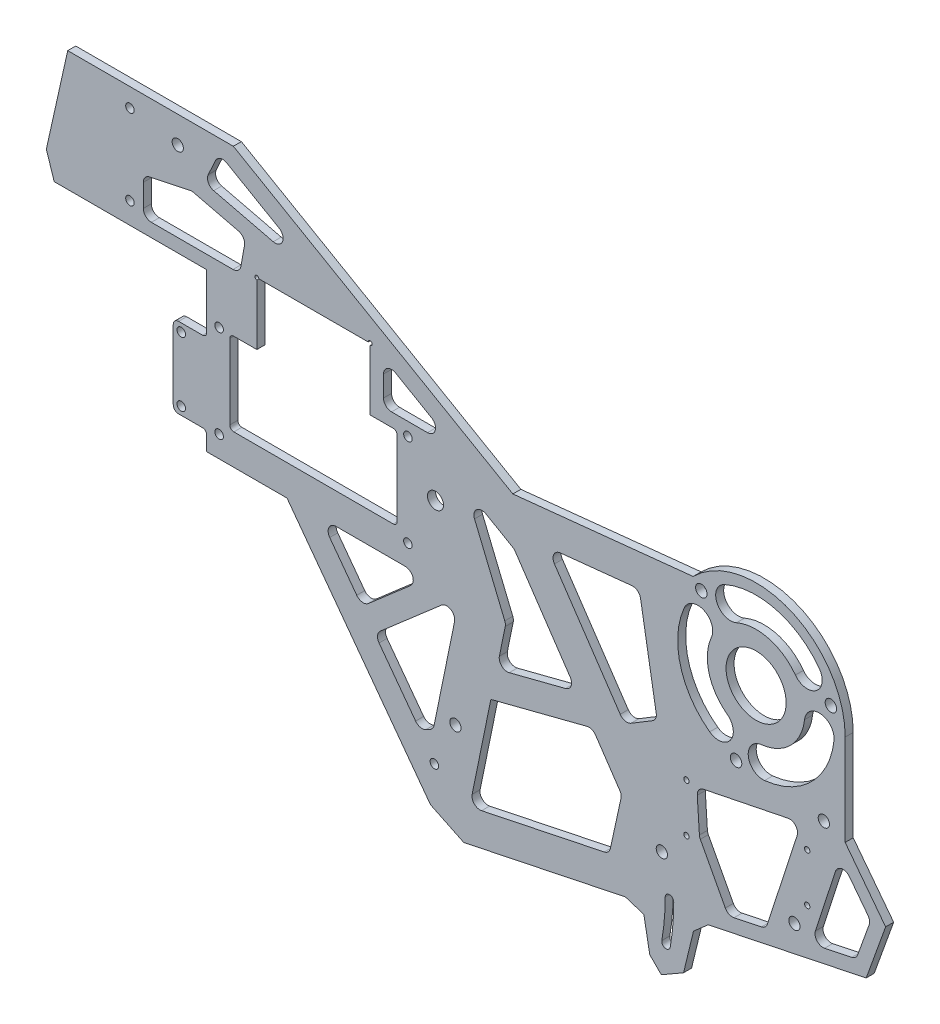
SolidWorks part; units mm, degrees
material "Thornel Mat VMA"
ref_plane "Front Plane" through (0, 0, 0) normal (0, 0, 1) x (1, 0, 0)
ref_plane "Top Plane" through (0, 0, 0) normal (0, 1, 0) x (1, 0, 0)
ref_plane "Right Plane" through (0, 0, 0) normal (1, 0, 0) x (0, 0, -1)
sketch "Sketch1" plane through (0, 0, 0) normal (0, 0, 1) x (1, 0, 0)
  line L1 (20.2869, 47.6) -> (204.7012, 47.6)
  line L2 (20.2869, 47.6) -> (20.2869, -36.0143)
  line L3 (20.2869, -36.0143) -> (204.7012, -36.0143)
  line L4 (204.7012, 47.6) -> (204.7012, -36.0143)
extrude "Boss-Extrude1" add sketch "Sketch1" along normal blind 3
sketch "Sketch2" plane through (0, 0, 0) normal (0, 0, -1) x (-1, 0, 0)
  circle A0 centre (-24.1169, 24) radius 3
  dimension "D1" = 6
extrude "Cut-Extrude1" cut sketch "Sketch2" against normal blind 70
sketch "Sketch3" plane through (0, 0, 3) normal (0, 0, 1) x (1, 0, 0)
  line L0 (24.1169, 24) -> (144.1169, 24) construction
  circle A0 centre (144.1169, 24) radius 11.25
  dimension "D2" = 22.5
  dimension "D1" = 120
extrude "Cut-Extrude2" cut sketch "Sketch3" against normal blind 3
sketch "Sketch4" plane through (0, 0, 3) normal (0, 0, 1) x (1, 0, 0)
  line L0 (-61.5431, 47.6) -> (-61.5431, -3) construction
  line L1 (-61.5431, 56) -> (-61.5431, 34)
  line L2 (-61.5431, 4) -> (-61.5431, -26)
  line L3 (-61.5431, 34) -> (-72.0431, 34)
  line L5 (-61.5431, 4) -> (-72.0431, 4)
  line L6 (-74.0431, 32) -> (-74.0431, 6)
  line L7 (-51.5431, 101) -> (-121.5431, 101)
  line L8 (-121.5431, 101) -> (-121.5431, 56)
  line L9 (-121.5431, 56) -> (-61.5431, 56)
  line L10 (-51.5431, 101) -> (40.9484, 47.6)
  line L11 (20.2869, 47.6) -> (20.2869, -36.0143)
  line L12 (20.2869, -36.0143) -> (204.7012, -36.0143)
  line L13 (204.7012, -36.0143) -> (204.7012, 47.6)
  line L14 (204.7012, 47.6) -> (20.2869, 47.6)
  line L15 (20.2869, 47.6) -> (20.2869, -36.0143)
  line L16 (20.2869, -36.0143) -> (204.7012, -36.0143)
  line L18 (40.9484, 47.6) -> (20.2869, 47.6)
  line L19 (-61.5431, -26) -> (34.7012, -81.5667)
  line L20 (34.7012, -81.5667) -> (204.7012, -81.5667)
  line L21 (204.7012, -81.5667) -> (204.7012, -36.0143)
  line L22 (-85.0431, 56) -> (-64.7431, 56) construction
  circle A0 centre (-71.0431, 31) radius 1.6
  circle A1 centre (-71.0431, 7) radius 1.6
  arc A2 (-72.0431, 4) -> (-74.0431, 6) centre (-72.0431, 6) cw
  arc A3 (-72.0431, 34) -> (-74.0431, 32) centre (-72.0431, 32) ccw
  dimension "D1" = 3.2
  dimension "D2" = 3
  dimension "D5" = 2
  dimension "D3" = 3
  dimension "D4" = 3
  dimension "D7" = 60
  dimension "D8" = 45
  dimension "D9" = 30
  dimension "D10" = 30
  dimension "D11" = 70
  dimension "D12" = 170
  dimension "D6" = 0
extrude "Boss-Extrude2" add sketch "Sketch4" against normal blind 3
sketch "Sketch5" plane through (0, 0, 3) normal (0, 0, 1) x (1, 0, 0)
  line L0 (-0.5431, 62.6) -> (-42.5431, 62.6) construction
  line L1 (8.2869, 8.5) -> (-51.3731, 8.5)
  line L2 (9.7869, 10) -> (9.7869, 38)
  line L3 (8.2869, 39.5) -> (-0.3431, 39.5)
  line L4 (-52.8731, 10) -> (-52.8731, 38)
  line L5 (-41.9931, 62.8) -> (-1.0931, 62.8)
  line L6 (-42.7431, 62.05) -> (-42.7431, 39.5)
  line L8 (-0.3431, 62.05) -> (-0.3431, 39.5)
  line L9 (-42.5431, 57.6) -> (-42.5431, 52.6) construction
  line L10 (-0.5431, 62.6) -> (-0.5431, 57.6) construction
  line L11 (-42.7431, 39.5) -> (-51.3731, 39.5)
  line L13 (7.7869, 47.6) -> (7.7869, -3) construction
  line L14 (-50.8731, -3) -> (-50.8731, 47.6) construction
  line L15 (8.4569, 34.5) -> (-51.5431, 34.5) construction
  line L16 (-51.5431, 13.5) -> (8.4569, 13.5) construction
  arc A0 (9.7869, 38) -> (8.2869, 39.5) centre (8.2869, 38) ccw
  arc A1 (8.2869, 8.5) -> (9.7869, 10) centre (8.2869, 10) ccw
  arc A2 (-51.3731, 8.5) -> (-52.8731, 10) centre (-51.3731, 10) cw
  arc A3 (-51.3731, 39.5) -> (-52.8731, 38) centre (-51.3731, 38) ccw
  arc A4 (-41.9931, 62.8) -> (-42.7431, 62.05) centre (-42.7431, 62.8) ccw
  arc A6 (-1.0931, 62.8) -> (-0.3431, 62.05) centre (-0.3431, 62.8) cw
  dimension "D8" = 1.5
  dimension "D9" = 1.5
  dimension "D10" = 0.75
  dimension "D1" = 0.2
  dimension "D2" = 0.2
  dimension "D3" = 0.2
  dimension "D4" = 2
  dimension "D5" = 2
  dimension "D6" = 5
  dimension "D7" = 5
extrude "Cut-Extrude3" cut sketch "Sketch5" against normal blind 10 contours L8 L5 L6 L3 | L4 L1 L2 L3
sketch "Sketch6" plane through (0, 0, 3) normal (0, 0, 1) x (1, 0, 0)
  line L0 (-61.5431, -3) -> (-50.8731, -3) construction
  line L1 (13.7869, 5) -> (-56.8731, 5) construction
  line L2 (13.7869, 5) -> (13.7869, 39.6) construction
  line L3 (13.7869, 39.6) -> (-56.8731, 39.6) construction
  line L4 (-56.8731, 5) -> (-56.8731, 39.6) construction
  line L5 (-61.5431, 47.6) -> (-50.8731, 47.6) construction
  line L6 (-52.8731, 10) -> (-52.8731, 38) construction
  line L7 (9.7869, 10) -> (9.7869, 38) construction
  circle A0 centre (13.7869, 5) radius 1.6
  circle A1 centre (13.7869, 39.6) radius 1.6
  circle A2 centre (-56.8731, 5) radius 1.6
  circle A3 centre (-56.8731, 39.6) radius 1.6
  dimension "D5" = 3.2
  dimension "D1" = 8
  dimension "D2" = 8
  dimension "D3" = 4
  dimension "D4" = 4
extrude "Cut-Extrude4" cut sketch "Sketch6" against normal blind 3
fillet "Fillet1" radius 1.5 2 edges at (-61.5431, 4, 1.5) (-61.5431, 34, 1.5)
sketch "Sketch8" plane through (0, 0, 3) normal (0, 0, 1) x (1, 0, 0)
  circle A0 centre (-90.2431, 94) radius 1.6
  circle A1 centre (-90.2431, 64) radius 1.6
  dimension "D1" = 3.2
extrude "Cut-Extrude6" cut sketch "Sketch8" against normal blind 12
sketch "Sketch9" plane through (0, 0, 0) normal (0, 0, -1) x (-1, 0, 0)
  circle A0 centre (-172.1287, 31.5058) radius 2.15
  circle A1 centre (-123.6108, 44.5061) radius 2.15
  circle A2 centre (-136.6111, -4.0118) radius 2.15
  dimension "D1" = 4.3
extrude "Cut-Extrude7" cut sketch "Sketch9" against normal blind 12
sketch "Sketch10" plane through (0, 0, 0) normal (0, 0, -1) x (-1, 0, 0)
  line L0 (-204.7012, 47.6) -> (-40.9484, 47.6) construction
  line L1 (-167.6809, 47.6) -> (-120.5529, 47.6)
  arc A0 (-120.5529, 47.6) -> (-167.6809, 47.6) centre (-144.1169, 24) ccw
  dimension "D1" = 66.7
extrude "Boss-Extrude3" add sketch "Sketch10" against normal blind 3
sketch "Sketch12" plane through (0, 0, 3) normal (0, 0, 1) x (1, 0, 0)
  line L0 (34.7012, -81.5667) -> (204.7012, -81.5667) construction
  circle A0 centre (23.7012, -61.5667) radius 1.6
  arc A1 (111.7012, -61.5667) -> (110.4134, -76.5667) centre (23.7012, -61.5667) cw construction
  arc A2 (110.1012, -61.5667) -> (108.8368, -76.294) centre (23.7012, -61.5667) cw
  arc A3 (113.3012, -61.5667) -> (111.99, -76.8394) centre (23.7012, -61.5667) cw
  arc A4 (113.3012, -61.5667) -> (110.1012, -61.5667) centre (111.7012, -61.5667) ccw
  arc A5 (111.99, -76.8394) -> (108.8368, -76.294) centre (110.4134, -76.5667) cw
  dimension "D1" = 3.2
  dimension "D2" = 1.6
  dimension "D3" = 5
extrude "Cut-Extrude8" cut sketch "Sketch12" against normal blind 10
sketch "Sketch13" plane through (0, 0, 0) normal (0, 0, -1) x (-1, 0, 0)
  circle A0 centre (-163.2569, -19.6667) radius 1
  circle A1 centre (-163.2569, -37.6667) radius 1
  circle A2 centre (-118.0569, -19.6667) radius 1
  circle A3 centre (-118.0569, -37.6667) radius 1
  dimension "D1" = 2
extrude "Cut-Extrude9" cut sketch "Sketch13" against normal blind 10
sketch "Sketch14" plane through (0, 0, 3) normal (0, 0, 1) x (1, 0, 0)
  line L0 (-78.9115, 93.4551) -> (-78.9115, 81.4862)
  line L1 (-78.9115, 81.4862) -> (-54.4003, 81.4862)
  line L2 (-54.4003, 81.4862) -> (-23.8974, 71.6817)
  line L3 (-23.8974, 71.6817) -> (-52.5178, 93.4551)
  line L4 (-52.5178, 93.4551) -> (-78.9115, 93.4551)
  line L5 (-78.9115, 72.578) -> (-70.6821, 62.8507)
  line L6 (-70.6821, 62.8507) -> (-60.2008, 63.6802)
  line L7 (-60.2008, 63.6802) -> (-54.4003, 58.7304)
  line L8 (-54.4003, 58.7304) -> (-54.4003, 45.3567)
  line L9 (-54.4003, 45.3567) -> (-47.2283, 45.9243)
  line L10 (-47.2283, 45.9243) -> (-47.2283, 69.3356)
  line L11 (-47.2283, 69.3356) -> (-63.8202, 74.1615)
  line L12 (-63.8202, 74.1615) -> (-78.9115, 72.578)
  line L13 (4.6513, 57.6299) -> (6.1633, 43.2207)
  line L14 (6.1633, 43.2207) -> (24.148, 52.0435)
  line L15 (24.148, 52.0435) -> (4.6513, 57.6299)
  line L16 (-45.3699, 1.9614) -> (-38.5507, -11.9389)
  line L17 (-38.5507, -11.9389) -> (-7.827, 0.9897)
  line L18 (-7.827, 0.9897) -> (-45.3699, 1.9614)
  line L19 (25.5976, 0.9897) -> (-23.1889, -25.4945)
  line L20 (-23.1889, -25.4945) -> (15.1557, -49.1549)
  line L21 (15.1557, -49.1549) -> (22.7058, -35.0463)
  line L22 (22.7058, -35.0463) -> (25.5976, 0.9897)
  line L23 (40.0766, 31.4181) -> (50.4041, -2.9024)
  line L24 (50.4041, -2.9024) -> (40.0766, -53.4167)
  line L25 (40.0766, -53.4167) -> (100.5808, -42.9603)
  line L26 (100.5808, -42.9603) -> (93.2786, -7.1794)
  line L27 (93.2786, -7.1794) -> (104.3379, 31.4181)
  line L28 (104.3379, 31.4181) -> (40.0766, 31.4181)
  line L29 (128.8509, 35.2778) -> (117.8298, 30.6401)
  line L30 (117.8298, 30.6401) -> (110.8301, -3.5975)
  line L31 (110.8301, -3.5975) -> (123.3404, -3.5975)
  line L32 (123.3404, -3.5975) -> (126.888, 28.7882)
  line L33 (126.888, 28.7882) -> (129.9965, 31.4181)
  line L34 (129.9965, 31.4181) -> (128.8509, 35.2778)
  line L35 (108.9142, -14.8646) -> (113.6543, -38.091)
  line L36 (113.6543, -38.091) -> (133.5452, -30.7552)
  line L37 (133.5452, -30.7552) -> (123.8212, -12.8427)
  line L38 (123.8212, -12.8427) -> (108.9142, -14.8646)
  line L39 (132.2934, -12.8427) -> (142.2048, -27.2848)
  line L40 (142.2048, -27.2848) -> (145.1405, -21.7989)
  line L41 (145.1405, -21.7989) -> (132.2934, -12.8427)
  line L42 (134.3797, 10.2416) -> (133.5452, 2.6233)
  line L43 (133.5452, 2.6233) -> (157.3171, -7.1794)
  line L44 (157.3171, -7.1794) -> (160.734, -2.2781)
  line L45 (160.734, -2.2781) -> (134.3797, 10.2416)
  line L46 (175.8668, 40.8797) -> (188.507, 15.1137)
  line L47 (188.507, 15.1137) -> (177.3665, -23.7672)
  line L48 (177.3665, -23.7672) -> (157.3171, -46.7471)
  line L49 (157.3171, -46.7471) -> (120.319, -62.316)
  line L50 (120.319, -62.316) -> (116.3677, -89.9345)
  line L51 (116.3677, -89.9345) -> (104.3379, -88.2135)
  line L52 (104.3379, -88.2135) -> (104.3379, -66.6352)
  line L53 (104.3379, -66.6352) -> (10.5955, -82.8358)
sketch "Sketch16" plane through (0, 0, 3) normal (0, 0, 1) x (1, 0, 0)
  line L0 (185.3256, -50.1785) -> (192.6101, -29.967)
  line L1 (192.6101, -29.967) -> (177.4666, -10.1551)
  line L2 (177.4666, -10.1551) -> (177.4669, 23.9998)
  line L3 (185.3256, -50.1785) -> (126.1767, -62.5044)
  line L4 (126.1767, -62.5044) -> (120.6914, -67.2922)
  line L5 (120.6914, -67.2922) -> (116.9293, -82.819)
  line L6 (116.9293, -82.819) -> (107.0809, -86.6499)
  line L7 (107.0809, -86.6499) -> (104.3379, -83.2478)
  line L8 (104.3379, -83.2478) -> (102.1139, -71.1635)
  line L9 (102.1139, -71.1635) -> (95.1728, -68.9652)
  line L10 (95.1728, -68.9652) -> (34.7012, -81.5667)
  line L11 (34.7012, -81.5667) -> (-10.3776, -59.7831)
  line L12 (-10.3776, -59.7831) -> (-61.5431, 0.5)
  line L13 (-61.5431, 2.5) -> (-61.5431, -26) construction
  line L14 (167.6809, 47.6) -> (204.7012, 47.6)
  line L15 (204.7012, 47.6) -> (204.7012, -81.5667)
  line L16 (204.7012, -81.5667) -> (109.0158, -101.5063)
  line L17 (109.0158, -101.5063) -> (-44.9012, -81.5667)
  line L18 (-44.9012, -81.5667) -> (-83.4799, -7.1794)
  line L19 (-83.4799, -7.1794) -> (-61.5431, 0.5)
  line L20 (181.5695, -45.8538) -> (186.9817, -30.837)
  line L21 (186.9817, -30.837) -> (175.5875, -15.9302)
  line L22 (175.5875, -15.9302) -> (164.7077, -49.3676)
  line L23 (164.7077, -49.3676) -> (181.5695, -45.8538)
  line L24 (147.7862, -52.8938) -> (133.6464, -55.8404)
  line L25 (133.6464, -55.8404) -> (122.94, -35.6877)
  line L26 (122.94, -35.6877) -> (121.9284, -19.9448)
  line L27 (121.9284, -19.9448) -> (161.094, -11.9946)
  line L28 (161.094, -11.9946) -> (147.7862, -52.8938)
  line L29 (89.1667, -57.959) -> (93.8268, -36.5614)
  line L30 (93.8268, -36.5614) -> (82.8591, -20.3346)
  line L31 (82.8591, -20.3346) -> (44.8433, -30.1016)
  line L32 (44.8433, -30.1016) -> (36.9222, -68.8461)
  line L33 (36.9222, -68.8461) -> (89.1667, -57.959)
  line L34 (76.9131, -11.5374) -> (47.0712, -19.2044)
  line L35 (47.0712, -19.2044) -> (50.4041, -2.9024)
  line L36 (50.4041, -2.9024) -> (35.3223, 33.6)
  line L37 (35.3223, 33.6) -> (46.4046, 33.6)
  line L38 (46.4046, 33.6) -> (76.9131, -11.5374)
  line L39 (94.8609, -13.0907) -> (107.0873, -5.7113)
  line L40 (107.0873, -5.7113) -> (100.3631, 33.6)
  line L41 (100.3631, 33.6) -> (63.3026, 33.6)
  line L42 (63.3026, 33.6) -> (94.8609, -13.0907)
  line L43 (12.3235, -57.4254) -> (22.136, -41.3202)
  line L44 (22.136, -41.3202) -> (30.031, -2.7036)
  line L45 (30.031, -2.7036) -> (-25.069, -30.1108)
  line L46 (-25.069, -30.1108) -> (-11.7658, -45.7846)
  line L47 (-11.7658, -45.7846) -> (12.3235, -57.4254)
  line L48 (-31.7345, -22.2575) -> (1.7886, -5.5828)
  line L49 (1.7886, -5.5828) -> (-2.1286, 0.5)
  line L50 (-2.1286, 0.5) -> (-41.5431, 0.5)
  line L51 (-41.5431, 0.5) -> (-41.5431, -10.701)
  line L52 (-41.5431, -10.701) -> (-31.7345, -22.2575)
  line L53 (32.3178, 44.5) -> (4.6569, 44.5)
  line L54 (4.6569, 44.5) -> (4.6569, 60.47)
  line L55 (4.6569, 60.47) -> (32.3178, 44.5)
  line L56 (-16.3481, 72.5973) -> (-56.8804, 95.9986)
  line L57 (-56.8804, 95.9986) -> (-62.4567, 83.7818)
  line L58 (-62.4567, 83.7818) -> (-16.3481, 72.5973)
  line L59 (-49.1617, 61) -> (-46.8615, 73.8249)
  line L60 (-46.8615, 73.8249) -> (-67.0805, 78.7295)
  line L61 (-67.0805, 78.7295) -> (-85.2431, 74.8953)
  line L62 (-85.2431, 74.8953) -> (-85.2431, 61)
  line L63 (-85.2431, 61) -> (-49.1617, 61)
  line L65 (110.4134, -76.5667) -> (116.9293, -82.819) construction
  line L66 (110.4134, -76.5667) -> (104.3379, -83.2478) construction
  line L67 (120.6914, -67.2922) -> (102.1139, -71.1635) construction
  line L68 (8.2869, 8.5) -> (-51.3731, 8.5) construction
  line L69 (50.4041, -2.9024) -> (40.0766, -53.4167) construction
  line L70 (104.3379, -88.2135) -> (104.3379, -66.6352) construction
  line L72 (8.2869, 39.5) -> (-0.3431, 39.5) construction
  line L73 (-0.3431, 62.05) -> (-0.3431, 39.5) construction
  line L74 (40.9484, 47.6) -> (-51.5431, 101) construction
  line L75 (-121.5431, 56) -> (-61.5431, 56) construction
  line L76 (120.5529, 47.6) -> (40.9484, 47.6) construction
  circle A0 centre (144.1169, 24) radius 33.35 construction
  arc A1 (177.4669, 23.9998) -> (167.6809, 47.6) centre (144.1169, 24) ccw
  circle A2 centre (106.5214, -50.3836) radius 2.1 construction
  circle A3 centre (164.7077, -10.5397) radius 2.1 construction
  circle A4 centre (30.031, -49.0844) radius 2.1 construction
  circle A5 centre (-75.4287, 89.9176) radius 2.1 construction
  circle A6 centre (163.2569, -37.6667) radius 1 construction
  circle A7 centre (118.0569, -37.6667) radius 1 construction
  circle A8 centre (-90.2431, 64) radius 1.6 construction
  arc A9 (-41.9931, 62.8) -> (-42.7431, 62.05) centre (-42.7431, 62.8) ccw construction
  dimension "D1" = 4.2
  dimension "D5" = 5
  dimension "D2" = 5
  dimension "D3" = 5
  dimension "D4" = 5
  dimension "D6" = 15
  dimension "D7" = 5
  dimension "D8" = 12
  dimension "D9" = 10
  dimension "D10" = 14
  dimension "D11" = 8
  dimension "D12" = 10
  dimension "D13" = 8
  dimension "D14" = 20
  dimension "D15" = 20
  dimension "D16" = 12
  dimension "D17" = 5
  dimension "D18" = 5
  dimension "D19" = 7
  dimension "D20" = 5
  dimension "D21" = 5
  dimension "D22" = 6
  dimension "D23" = 6
  dimension "D24" = 14
  dimension "D25" = 2
extrude "Cut-Extrude10" cut sketch "Sketch16" against normal blind 10
fillet "Fillet2" radius 3 43 edges at (175.5875, -15.9302, 1.5) (186.9817, -30.837, 1.5) (164.7077, -49.3676, 1.5) (181.5695, -45.8538, 1.5) (121.9284, -19.9448, 1.5) (122.94, -35.6877, 1.5) (133.6464, -55.8404, 1.5) (147.7862, -52.8938, 1.5) (94.8609, -13.0907, 1.5) (63.3026, 33.6, 1.5) (35.3223, 33.6, 1.5) (76.9131, -11.5374, 1.5) (89.1667, -57.959, 1.5) (36.9222, -68.8461, 1.5) (50.4041, -2.9024, 1.5) (47.0712, -19.2044, 1.5) (93.8268, -36.5614, 1.5) (82.8591, -20.3346, 1.5) (107.0873, -5.7113, 1.5) (100.3631, 33.6, 1.5) (161.094, -11.9946, 1.5) (46.4046, 33.6, 1.5) (30.031, -2.7036, 1.5) (-25.069, -30.1108, 1.5) (22.136, -41.3202, 1.5) (12.3235, -57.4254, 1.5) (-11.7658, -45.7846, 1.5) (-41.5431, -10.701, 1.5) (-31.7345, -22.2575, 1.5) (1.7886, -5.5828, 1.5) (-2.1286, 0.5, 1.5) (-41.5431, 0.5, 1.5) (4.6569, 60.47, 1.5) (32.3178, 44.5, 1.5) (4.6569, 44.5, 1.5) (-85.2431, 61, 1.5) (-46.8615, 73.8249, 1.5) (-49.1617, 61, 1.5) (-67.0805, 78.7295, 1.5) (-85.2431, 74.8953, 1.5) (-56.8804, 95.9986, 1.5) (-62.4567, 83.7818, 1.5) (-16.3481, 72.5973, 1.5)
sketch "Sketch17" plane through (0, 0, 3) normal (0, 0, 1) x (1, 0, 0)
  line L0 (34.7012, -81.5667) -> (-10.3776, -59.7831)
  line L1 (-10.3776, -59.7831) -> (-17.4388, -51.4637)
  line L2 (-17.4388, -51.4637) -> (-61.5431, 0.5) construction
  line L3 (-11.1945, -46.0607) -> (9.8726, -56.241) construction
  line L4 (-17.4388, -51.4637) -> (34.7012, -81.5667) construction
  line L5 (-17.4388, -51.4637) -> (34.7012, -81.5667)
extrude "Boss-Extrude4" add sketch "Sketch17" against normal blind 3
sketch "Sketch18" plane through (0, 0, 3) normal (0, 0, 1) x (1, 0, 0)
  line L0 (-51.5431, 101) -> (-121.5431, 101) construction
  line L1 (-58.251, 92.9958) -> (-60.9482, 87.0866) construction
  line L2 (13.7398, -55.1008) -> (21.8636, -41.7673) construction
  line L3 (44.8433, -30.1016) -> (37.8357, -64.3779) construction
  line L4 (89.5808, -56.0575) -> (93.5536, -37.8159) construction
  line L5 (123.2431, -36.2582) -> (132.5898, -53.8515) construction
  line L6 (173.8201, -21.362) -> (166.3088, -44.4468) construction
  line L7 (177.4669, 23.9998) -> (177.4666, -10.1551) construction
  line L8 (156.0528, -13.0179) -> (124.4933, -19.4241) construction
  circle A0 centre (31.5838, -45.033) radius 2.1
  circle A1 centre (-72.3529, 91) radius 2.1
  circle A2 centre (108.8401, -47.5134) radius 2.1
  circle A3 centre (158.4664, -45.9257) radius 2.1
  circle A4 centre (144.1169, 24) radius 33.35 construction
  circle A5 centre (169.4666, -7.2338) radius 2.1
  dimension "D1" = 4.2
  dimension "D2" = 10
  dimension "D3" = 12
  dimension "D4" = 10
  dimension "D5" = 10
  dimension "D6" = 17
  dimension "D7" = 18
  dimension "D8" = 7
  dimension "D9" = 19
  dimension "D10" = 8
  dimension "D11" = 3
extrude "Cut-Extrude11" cut sketch "Sketch18" against normal blind 3
sketch "Sketch19" plane through (0, 0, 3) normal (0, 0, 1) x (1, 0, 0)
  circle A0 centre (144.1169, 24) radius 29.35
  circle A1 centre (144.1169, 24) radius 18.25
  arc A2 (132.3018, 50.8668) -> (136.7702, 40.706) centre (134.536, 45.7864) ccw
  arc A3 (167.7824, 41.3598) -> (158.8323, 34.7944) centre (163.3073, 38.0771) cw
  arc A4 (162.258, 22.0094) -> (173.2918, 20.7987) centre (167.7749, 21.4041) cw
  arc A5 (146.1075, 5.8589) -> (147.3182, -5.1749) centre (146.7128, 0.342) ccw
  arc A6 (133.3224, 9.2846) -> (126.757, 0.3344) centre (130.0397, 4.8095) cw
  arc A7 (127.4109, 31.3467) -> (117.25, 35.8151) centre (122.3305, 33.5809) ccw
  arc A8 (177.4669, 23.9998) -> (120.5529, 47.6) centre (144.1169, 24) ccw construction
  circle A9 centre (144.1169, 24) radius 11.25 construction
  circle A10 centre (172.1287, 31.5058) radius 2.15 construction
  circle A11 centre (123.6108, 44.5061) radius 2.15 construction
  circle A12 centre (136.6111, -4.0118) radius 2.15 construction
  dimension "D1" = 4
  dimension "D2" = 7
  dimension "D8" = 11
  dimension "D3" = 11
  dimension "D4" = 11
  dimension "D5" = 11
  dimension "D6" = 11
  dimension "D7" = 11
extrude "Cut-Extrude12" cut sketch "Sketch19" against normal blind 3 contours A3 A0 A2 A1 | A1 A7 A0 A6 | A1 A5 A0 A4
sketch "Sketch20" plane through (0, 0, 3) normal (0, 0, 1) x (1, 0, 0)
  line L4 (-121.5431, 101) -> (-113.5431, 101)
  line L5 (-113.5431, 101) -> (-121.5431, 65.0628)
  line L6 (-121.5431, 65.0628) -> (-118.5984, 56)
  line L7 (-118.5984, 56) -> (-121.5431, 56)
  line L8 (-121.5431, 56) -> (-121.5431, 101)
  line L9 (-121.5431, 101) -> (-121.5431, 56) construction
  line L10 (-121.5431, 56) -> (-61.5431, 56) construction
  line L11 (-51.5431, 101) -> (-121.5431, 101) construction
  dimension "D2" = 72
  dimension "D3" = 77.45
  dimension "D4" = 8
extrude "Cut-Extrude13" cut sketch "Sketch20" against normal blind 10 contours L8 L5 L4 | L8 L7 L6
sketch "Sketch21" plane through (0, 0, 3) normal (0, 0, 1) x (1, 0, 0)
  line L0 (117.2327, -81.5667) -> (116.9665, -82.6658)
  line L1 (116.9665, -82.6658) -> (108.6575, -87.4629)
  line L2 (108.6575, -87.4629) -> (104.3143, -83.1198)
  line L3 (104.3143, -83.1198) -> (104.0285, -81.5667)
  line L4 (104.0285, -81.5667) -> (117.2327, -81.5667)
  line L5 (120.6914, -67.2922) -> (117.2327, -81.5667) construction
  line L6 (104.0285, -81.5667) -> (102.1139, -71.1635) construction
  line L7 (110.4134, -76.5667) -> (116.9665, -82.6658) construction
  line L8 (104.3143, -83.1198) -> (110.4134, -76.5667) construction
  dimension "D1" = 30
  dimension "D2" = 45
extrude "Boss-Extrude5" add sketch "Sketch21" against normal blind 3
sketch "Sketch22" plane through (0, 0, 3) normal (0, 0, 1) x (1, 0, 0)
  line L0 (22.246, -75.5479) -> (-29.7449, -5.3216)
  line L1 (-29.7449, -5.3216) -> (-61.5431, -5.3216)
  line L2 (-61.5431, -5.3216) -> (-61.5431, 0.5)
  line L4 (-61.5431, 2.5) -> (-61.5431, 0.5) construction
  line L6 (-10.3776, -59.7831) -> (34.7012, -81.5667) construction
  line L7 (22.246, -75.5479) -> (-101.253, -52.9562)
  line L8 (-101.253, -52.9562) -> (-61.5431, 0.5)
extrude "Cut-Extrude14" cut sketch "Sketch22" against normal blind 10
sketch "Sketch23" plane through (0, 0, 3) normal (0, 0, 1) x (1, 0, 0)
  line L0 (22.246, -75.5479) -> (-31.4636, -3)
  line L1 (-31.4636, -3) -> (-61.5431, -3)
  line L3 (-15.0734, -25.139) -> (-21.1166, -16.9761) construction
  line L4 (22.246, -75.5479) -> (19.933, -56.2587)
  line L5 (19.933, -56.2587) -> (25.986, -38.1223)
  line L6 (25.986, -38.1223) -> (34.1858, 1.8113)
  line L7 (34.1858, 1.8113) -> (9.3649, -1.4066)
  line L8 (9.3649, -1.4066) -> (0.0796, 0.5)
  line L9 (0.0796, 0.5) -> (-61.5431, 0.5)
  line L10 (-61.5431, 0.5) -> (-61.5431, -3)
  line L11 (-74.0431, 32) -> (-74.0431, 6) construction
  line L12 (-51.5431, 101) -> (-113.5431, 101) construction
  dimension "D1" = 42.5795
  dimension "D2" = 74.1227
  dimension "D3" = 83.408
  dimension "D4" = 93.9761
  dimension "D5" = 100.0291
  dimension "D6" = 108.2289
  dimension "D7" = 99.1887
  dimension "D8" = 102.4066
  dimension "D10" = 157.2587
extrude "Boss-Extrude7" add sketch "Sketch23" against normal blind 3
sketch "Sketch24" plane through (0, 0, 3) normal (0, 0, 1) x (1, 0, 0)
  line L0 (-41.5431, -3) -> (-58.5725, -3)
  line L1 (-58.5725, -3) -> (-58.5725, -18.775)
  line L2 (-58.5725, -18.775) -> (-41.5431, -18.775)
  line L3 (-41.5431, -18.775) -> (-41.5431, -3)
extrude "Cut-Extrude15" cut sketch "Sketch24" against normal blind 3
sketch "Sketch25" plane through (0, 0, 3) normal (0, 0, 1) x (1, 0, 0)
  line L0 (16.6752, -51.2169) -> (2.9955, -32.7392)
  line L1 (3.44, -28.6886) -> (26.3557, -8.796)
  line L2 (31.2615, -11.6624) -> (23.5944, -49.1642)
  line L3 (22.1083, -51.1879) -> (20.5394, -52.0565)
  line L4 (-0.9821, -21.9336) -> (14.7631, -8.2655)
  line L5 (12.7965, -3) -> (-13.0677, -3)
  line L6 (-15.4789, -7.785) -> (-5.3599, -21.4532)
  line L7 (44.8433, -30.1016) -> (37.8357, -64.3779) construction
  line L8 (8.2869, 8.5) -> (-51.3731, 8.5) construction
  line L9 (22.246, -75.5479) -> (-31.4636, -3) construction
  line L10 (-61.5431, -3) -> (-31.4636, -3) construction
  line L11 (-74.0431, 32) -> (-74.0431, 6) construction
  circle A0 centre (31.5838, -45.033) radius 2.1 construction
  arc A1 (-13.0677, -3) -> (-15.4789, -7.785) centre (-13.0677, -6) ccw
  arc A2 (-0.9821, -21.9336) -> (-5.3599, -21.4532) centre (-2.9488, -19.6681) cw
  arc A3 (14.7631, -8.2655) -> (12.7965, -3) centre (12.7965, -6) ccw
  arc A4 (2.9955, -32.7392) -> (3.44, -28.6886) centre (5.4066, -30.9541) cw
  arc A5 (26.3557, -8.796) -> (31.2615, -11.6624) centre (28.3223, -11.0615) cw
  arc A6 (16.6752, -51.2169) -> (20.5394, -52.0565) centre (19.0863, -49.4318) ccw
  arc A7 (23.5944, -49.1642) -> (22.1083, -51.1879) centre (20.6552, -48.5633) cw
  point P23 (-19.0214, -3)
  point P26 (-3.4306, -24.0591)
  point P31 (1.3439, -30.5082)
  point P34 (33.0325, -3)
  point P37 (18.2394, -53.3298)
  point P40 (23.3175, -50.5184)
  dimension "D5" = 3
  dimension "D1" = 10
  dimension "D2" = 7
  dimension "D3" = 8
  dimension "D4" = 70.6125
  dimension "D6" = 92.2825
  dimension "D8" = 97.3607
extrude "Cut-Extrude16" cut sketch "Sketch25" against normal blind 3
sketch "Sketch26" plane through (0, 0, 3) normal (0, 0, 1) x (1, 0, 0)
  line L0 (40.9484, 47.6) -> (53.0727, 40.6)
  line L1 (53.0727, 40.6) -> (120.5529, 47.6)
  line L2 (40.9484, 47.6) -> (120.5529, 47.6)
  line L3 (40.9484, 47.6) -> (-51.5431, 101) construction
  dimension "D1" = 7
extrude "Cut-Extrude17" cut sketch "Sketch26" against normal blind 3
sketch "Sketch27" plane through (0, 0, 3) normal (0, 0, 1) x (1, 0, 0)
  line L0 (101.2505, 28.412) -> (100.8633, 30.6761)
  line L1 (106.7424, -3.6944) -> (100.7898, 31.1058) construction
  line L2 (97.5967, 33.1543) -> (70.8103, 30.3756)
  line L3 (66.4657, 28.92) -> (93.265, -10.7296) construction
  line L4 (53.0727, 40.6) -> (120.5529, 47.6) construction
  line L5 (68.6343, 25.7116) -> (74.246, 17.4091)
  line L6 (43.0041, 29.0926) -> (52.9785, 23.3339)
  line L8 (74.5295, -8.011) -> (47.2968, 32.28) construction
  line L9 (53.0727, 40.6) -> (-51.5431, 101) construction
  line L10 (53.964, 22.4158) -> (60.8301, 12.2574)
  line L11 (38.7314, 25.349) -> (40.8011, 20.3397)
  line L12 (37.0352, 29.4544) -> (50.0538, -2.0546) construction
  line L13 (101.2505, 28.412) -> (110.1024, 37.9468)
  line L14 (110.1024, 37.9468) -> (55.5175, 34.9915)
  line L15 (55.5175, 34.9915) -> (74.246, 17.4091)
  line L16 (60.8301, 12.2574) -> (47.3983, 37.9468)
  line L17 (47.3983, 37.9468) -> (28.8837, 36.0262)
  line L18 (28.8837, 36.0262) -> (40.8011, 20.3397)
  line L19 (-85.2431, 72.4624) -> (-85.2431, 64) construction
  line L20 (-51.5431, 101) -> (-113.5431, 101) construction
  arc A0 (70.8103, 30.3756) -> (68.6343, 25.7116) centre (71.1198, 27.3916) ccw
  arc A1 (100.8633, 30.6761) -> (97.5967, 33.1543) centre (97.9062, 30.1703) ccw
  arc A2 (43.0041, 29.0926) -> (38.7314, 25.349) centre (41.5041, 26.4946) ccw
  arc A3 (52.9785, 23.3339) -> (53.964, 22.4158) centre (51.4785, 20.7358) cw
  point P12 (65.831, 29.8591)
  point P29 (53.577, 22.9883)
  dimension "D2" = 3
  dimension "D4" = 3
  dimension "D1" = 12
  dimension "D3" = 15
extrude "Boss-Extrude8" add sketch "Sketch27" against normal blind 3
